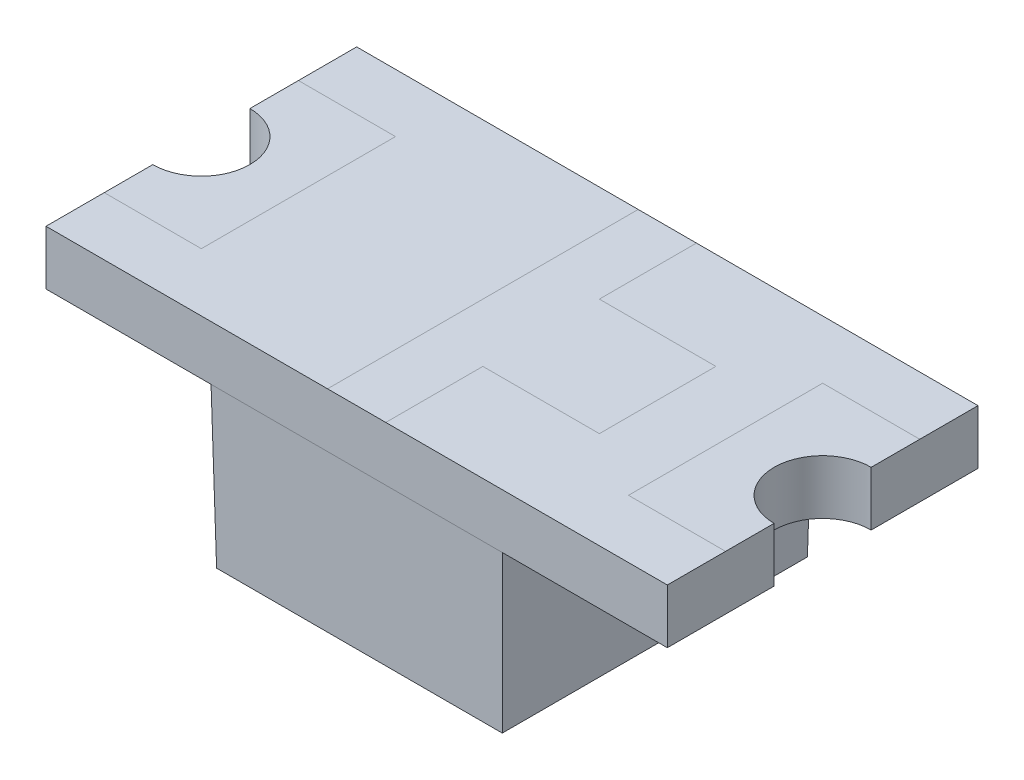
SolidWorks part; units mm, degrees
ref_plane "Front Plane" through (0, 0, 0) normal (0, 0, 1) x (1, 0, 0)
ref_plane "Top Plane" through (0, 0, 0) normal (0, 1, 0) x (1, 0, 0)
ref_plane "Right Plane" through (0, 0, 0) normal (1, 0, 0) x (0, 0, -1)
sketch "Sketch1" plane through (0, 0, 0) normal (0, 1, 0) x (1, 0, 0)
  line L1 (-1.6, 0.8) -> (1.6, 0.8)
  line L3 (-1.6, -0.8) -> (1.6, -0.8)
  line L5 (1.6, 0.8) -> (1.6, -0.8)
  line L6 (-1.6, 0.8) -> (-1.6, -0.8)
  dimension "D1" = 3.2
  dimension "D2" = 1.6
  dimension "D3" = 1.6
  dimension "D4" = 0.8
extrude "Boss-Extrude1" add sketch "Sketch1" along normal blind 0.28
sketch "Sketch2" plane through (0, 0, 0) normal (0, -1, 0) x (1, 0, 0)
  line L0 (-1.6, 0.8) -> (1.6, 0.8) construction
  line L1 (-0.75, 0.8) -> (0.75, 0.8)
  line L2 (-0.75, 0.8) -> (-0.75, -0.8)
  line L3 (-0.75, -0.8) -> (0.75, -0.8)
  line L4 (0.75, 0.8) -> (0.75, -0.8)
  line L5 (1.6, -0.8) -> (-1.6, -0.8) construction
  point P8 (0, 0.8)
  dimension "D1" = 1.5
extrude "Boss-Extrude2" add sketch "Sketch2" along normal blind 0.82 draft 1 separate body
sketch "Sketch3" plane through (0, 0, 0) normal (0, -1, 0) x (1, 0, 0)
  line L0 (1.6, 0.8) -> (1.6, -0.8) construction
  line L1 (0.15, 0.1) -> (0.35, 0.1)
  line L2 (0.15, 0.1) -> (0.15, -0.1)
  line L3 (0.15, -0.1) -> (0.35, -0.1)
  line L4 (0.35, 0.1) -> (0.35, -0.1)
  point P4 (0.15, 0)
  point P5 (0.25, 0.1)
  dimension "D1" = 0.2
  dimension "D2" = 1.35
extrude "Boss-Extrude3" add sketch "Sketch3" along normal blind 0.2 separate body
sketch "Sketch4" plane through (0, 0.28, 0) normal (0, 1, 0) x (1, 0, 0)
  line L1 (-1.6, 0.8) -> (-1.6, -0.8) construction
  line L6 (-1.6, -0.5) -> (-1.1, -0.5)
  line L7 (-1.1, -0.5) -> (-1.1, 0.5)
  line L8 (-1.1, 0.5) -> (-1.6, 0.5)
  line L9 (0, -0.8) -> (0, 0.8) construction
  line L10 (-1.6, -0.8) -> (1.6, -0.8) construction
  line L11 (1.6, 0.8) -> (-1.6, 0.8) construction
  line L16 (-1.6, 0.5) -> (-1.6, -0.5)
  line L24 (1.6, 0.5) -> (1.6, -0.5)
  line L26 (1.1, 0.5) -> (1.6, 0.5)
  line L27 (1.1, -0.5) -> (1.1, 0.5)
  line L28 (1.6, -0.5) -> (1.1, -0.5)
  line L29 (-0.15, -0.8) -> (-0.15, 0.8)
  line L30 (-0.15, 0.8) -> (0.15, 0.8)
  line L31 (0.15, 0.8) -> (0.15, 0.3)
  line L32 (0.15, 0.3) -> (0.75, 0.3)
  line L33 (0.75, 0.3) -> (0.75, -0.3)
  line L34 (0.75, -0.3) -> (0.15, -0.3)
  line L35 (0.15, -0.3) -> (0.15, -0.8)
  line L36 (0.15, -0.8) -> (-0.15, -0.8)
  line L40 (1.6, -0.8) -> (1.6, 0.8) construction
  point P18 (0, 0)
  dimension "D2" = 0.5
  dimension "D3" = 1
  dimension "D4" = 0.5
  dimension "D5" = 0.3
  dimension "D6" = 0.15
  dimension "D7" = 0.6
  dimension "D8" = 0.6
  dimension "D9" = 0.3
  dimension "D10" = 0.5
split line "Split Line1"
sketch "Sketch5" plane through (0, 0, 0) normal (0, -1, 0) x (1, 0, 0)
  line L0 (1.6, -0.8) -> (-1.6, -0.8) construction
  line L1 (-1.6, 0.8) -> (-0.75, 0.8)
  line L2 (-1.6, 0.8) -> (-1.6, -0.8)
  line L3 (-1.6, -0.8) -> (-0.75, -0.8)
  line L4 (-0.75, 0.8) -> (-0.75, -0.8)
  line L5 (-0.75, -0.8) -> (0.75, -0.8) construction
  line L6 (-0.75, 0.8) -> (-0.75, -0.8) construction
  line L7 (0.75, 0.8) -> (1.6, 0.8)
  line L8 (0.75, 0.8) -> (0.75, -0.8)
  line L9 (0.75, -0.8) -> (1.6, -0.8)
  line L10 (1.6, 0.8) -> (1.6, -0.8)
split line "Split Line2"
sketch "Sketch6" plane through (0, 0.28, 0) normal (0, 1, 0) x (1, 0, 0)
  line L0 (1.6, -0.5) -> (1.6, 0.5) construction
  line L1 (-1.6, 0.5) -> (-1.6, -0.5) construction
  circle A0 centre (-1.6, 0) radius 0.25
  circle A1 centre (1.6, 0) radius 0.25
  point P6 (-1.4505, -0.0358)
  point P9 (-1.6, 0)
  dimension "D1" = 0.5
extrude "Cut-Extrude1" cut sketch "Sketch6" against normal through all
